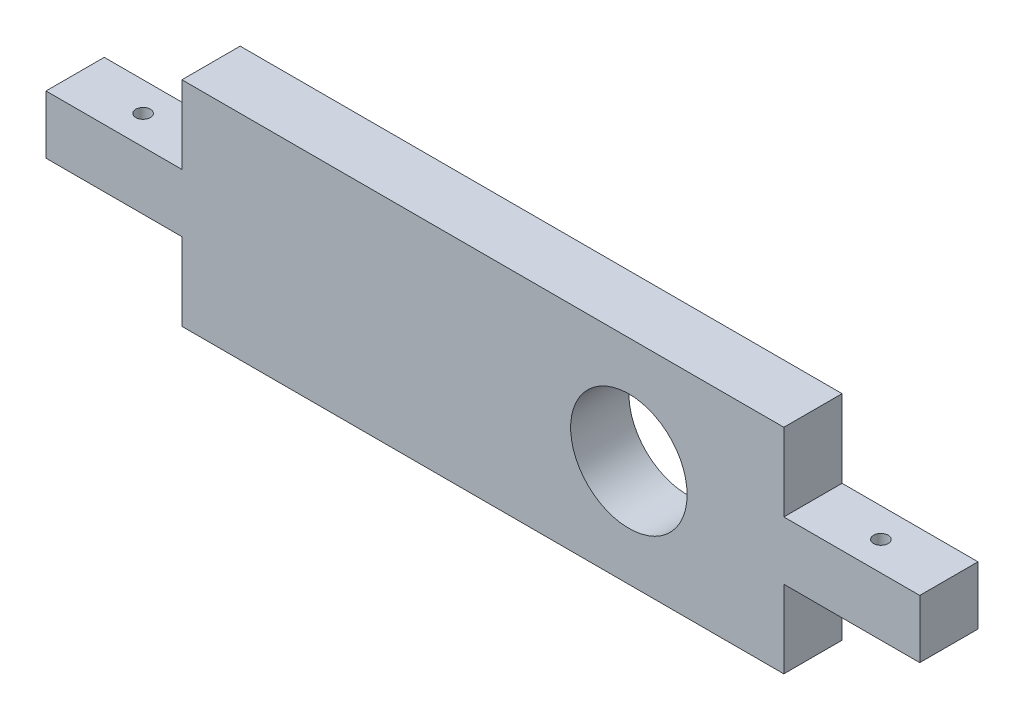
SolidWorks part; units mm, degrees
material "Oak"
ref_plane "Front" through (0, 0, 0) normal (0, 0, 1) x (1, 0, 0)
ref_plane "Top" through (0, 0, 0) normal (0, 1, 0) x (1, 0, 0)
ref_plane "Right" through (0, 0, 0) normal (1, 0, 0) x (0, 0, -1)
sketch "Sketch2" plane through (0, 0, 0) normal (0, 0, 1) x (1, 0, 0)
  line L1 (0, 0) -> (571.5, 0)
  line L2 (0, 0) -> (0, 139.7)
  line L3 (0, 139.7) -> (571.5, 139.7)
  line L4 (571.5, 0) -> (571.5, 139.7)
  dimension "D1" = 139.7
  dimension "D2" = 571.5
extrude "Boss-Extrude2" add sketch "Sketch2" along normal blind 38.1
sketch "Sketch3" plane through (0, 0, 38.1) normal (0, 0, 1) x (1, 0, 0)
  line L0 (0, 88.9) -> (88.9, 88.9)
  line L1 (0, 139.7) -> (0, 0) construction
  line L2 (88.9, 88.9) -> (88.9, 139.7)
  line L3 (571.5, 139.7) -> (0, 139.7) construction
  line L4 (88.9, 139.7) -> (0, 139.7)
  line L5 (0, 139.7) -> (0, 88.9)
  line L6 (0, 69.85) -> (571.5, 69.85) construction
  line L7 (571.5, 0) -> (571.5, 139.7) construction
  line L8 (285.75, 139.7) -> (285.75, 0) construction
  line L9 (0, 0) -> (571.5, 0) construction
  line L10 (571.5, 139.7) -> (571.5, 88.9)
  line L11 (482.6, 88.9) -> (482.6, 139.7)
  line L12 (571.5, 88.9) -> (482.6, 88.9)
  line L13 (482.6, 139.7) -> (571.5, 139.7)
  line L14 (571.5, 0) -> (571.5, 50.8)
  line L15 (571.5, 50.8) -> (482.6, 50.8)
  line L16 (482.6, 0) -> (571.5, 0)
  line L17 (482.6, 50.8) -> (482.6, 0)
  line L18 (88.9, 50.8) -> (88.9, 0)
  line L19 (88.9, 0) -> (0, 0)
  line L20 (0, 0) -> (0, 50.8)
  line L21 (0, 50.8) -> (88.9, 50.8)
  dimension "D1" = 50.8
  dimension "D2" = 88.9
extrude "Cut-Extrude1" cut sketch "Sketch3" against normal through all
sketch "Sketch4" plane through (0, 0, 38.1) normal (0, 0, 1) x (1, 0, 0)
  line L0 (571.5, 50.8) -> (571.5, 88.9) construction
  line L1 (482.6, 139.7) -> (88.9, 139.7) construction
  circle A0 centre (381.2476, 69.85) radius 38.1
  dimension "D3" = 76.2
  dimension "D1" = 69.85
  dimension "D2" = 190.2524
extrude "Cut-Extrude2" cut sketch "Sketch4" against normal through all
sketch "Sketch5" plane through (0, 50.8, 0) normal (0, -1, 0) x (-1, 0, 0)
  line L0 (-88.9, -38.1) -> (0, -38.1) construction
  line L1 (0, 0) -> (0, -38.1) construction
  circle A0 centre (-44.45, -19.05) radius 4.7625
  dimension "D3" = 9.525
  dimension "D1" = 19.05
  dimension "D2" = 44.45
extrude "Cut-Extrude3" cut sketch "Sketch5" against normal through all
sketch "Sketch6" plane through (0, 50.8, 0) normal (0, -1, 0) x (1, 0, 0)
  line L0 (571.5, 38.1) -> (482.6, 38.1) construction
  line L1 (571.5, 0) -> (571.5, 38.1) construction
  circle A0 centre (527.05, 19.05) radius 4.7625
  dimension "D3" = 9.525
  dimension "D1" = 19.05
  dimension "D2" = 44.45
extrude "Cut-Extrude4" cut sketch "Sketch6" against normal through all
